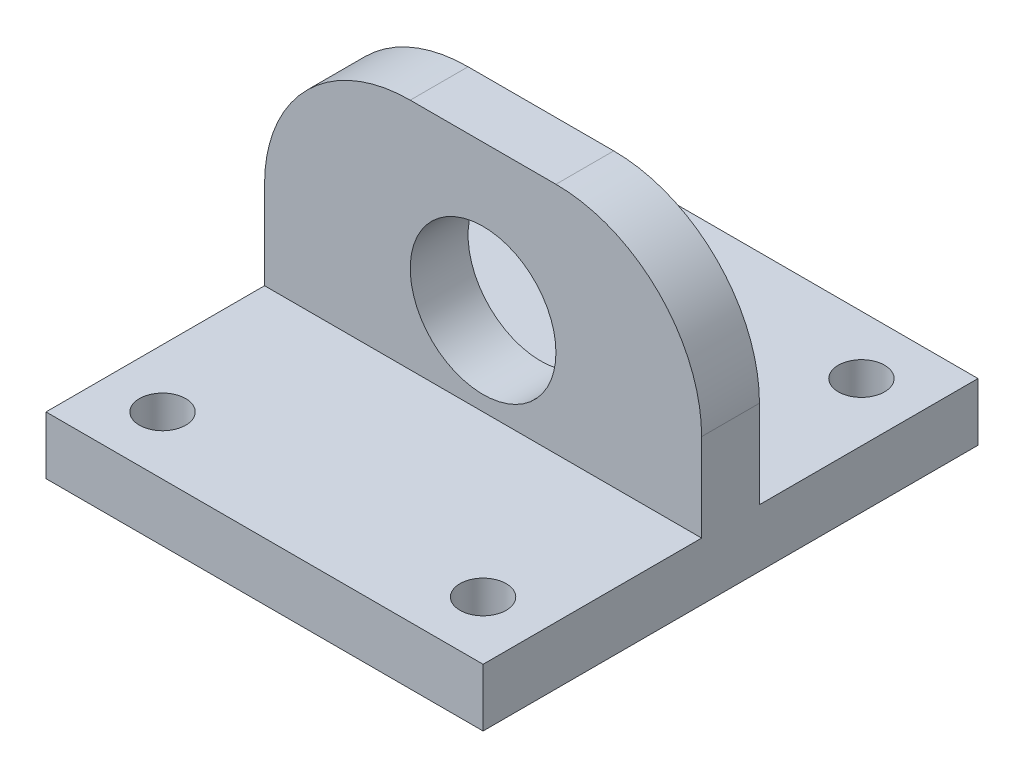
SolidWorks part; units mm, degrees
material "AISI 1020 Acero laminado en frío"
ref_plane "Alzado" through (0, 0, 0) normal (0, 0, 1) x (1, 0, 0)
ref_plane "Planta" through (0, 0, 0) normal (0, 1, 0) x (1, 0, 0)
ref_plane "Vista lateral" through (0, 0, 0) normal (1, 0, 0) x (0, 0, -1)
sketch "Croquis1" plane through (0, 0, 0) normal (0, 0, 1) x (1, 0, 0)
  line L1 (-30, -20) -> (30, -20)
  line L2 (-30, -20) -> (-30, 0)
  line L3 (-10, 20) -> (10, 20)
  line L4 (30, -20) -> (30, 0)
  line L5 (-30, -20) -> (30, 20) construction
  line L6 (-30, 20) -> (30, -20) construction
  circle A0 centre (0, 0) radius 10
  arc A1 (10, 20) -> (30, 0) centre (10, 0) cw
  arc A2 (-30, 0) -> (-10, 20) centre (-10, 0) cw
  point P0 (0, 0)
  dimension "D1" = 20
  dimension "D4" = 20
  dimension "D2" = 60
  dimension "D3" = 40
extrude "Saliente-Extruir1" add sketch "Croquis1" along normal mid plane 7.9375
sketch "Croquis3" plane through (0, 0, 0) normal (1, 0, 0) x (0, 0, -1)
  line L0 (0, 6.9029) -> (0, -39.1495) construction
  line L1 (-3.9688, -20) -> (-33.9688, -20)
  line L2 (-3.9688, -20) -> (-3.9688, -12.0625)
  line L3 (-3.9688, -12.0625) -> (-33.9688, -12.0625)
  line L4 (-33.9688, -20) -> (-33.9688, -12.0625)
  line L5 (3.9688, -12.0625) -> (33.9688, -12.0625)
  line L6 (33.9688, -20) -> (33.9688, -12.0625)
  line L7 (3.9688, -20) -> (33.9688, -20)
  line L8 (3.9688, -20) -> (3.9688, -12.0625)
  dimension "D1" = 7.9375
  dimension "D2" = 30
extrude "Saliente-Extruir2" add sketch "Croquis3" along normal mid plane 60
sketch "Croquis4" plane through (0, -20, 0) normal (0, -1, 0) x (1, 0, 0)
  line L0 (30, 33.9688) -> (-30, 33.9688) construction
  line L1 (-30, 33.9688) -> (-30, -33.9688) construction
  line L2 (0, 21.5866) -> (0, -20.9828) construction
  line L3 (35.8267, 0) -> (-48.3056, 0) construction
  circle A0 centre (-22, 25.9688) radius 3.175
  circle A1 centre (22, 25.9688) radius 3.175
  circle A2 centre (22, -25.9688) radius 3.175
  circle A3 centre (-22, -25.9688) radius 3.175
  dimension "D2" = 6.35
  dimension "D1" = 8
  dimension "D3" = 8
extrude "Cortar-Extruir1" cut sketch "Croquis4" against normal blind 60
